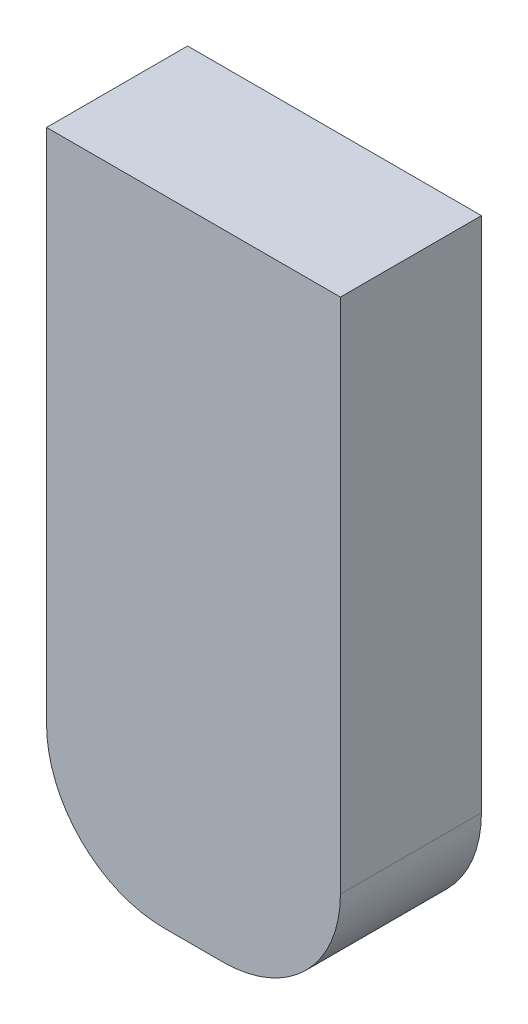
SolidWorks part; units mm, degrees
ref_plane "Front Plane" through (0, 0, 0) normal (0, 0, 1) x (1, 0, 0)
ref_plane "Top Plane" through (0, 0, 0) normal (0, 1, 0) x (1, 0, 0)
ref_plane "Right Plane" through (0, 0, 0) normal (1, 0, 0) x (0, 0, -1)
sketch "Sketch1" plane through (0, 0, 0) normal (0, 0, 1) x (1, 0, 0)
  line L1 (0, 0) -> (31.75, 0)
  line L2 (0, 0) -> (0, 68.58)
  line L3 (0, 68.58) -> (31.75, 68.58)
  line L4 (31.75, 0) -> (31.75, 68.58)
  dimension "D1" = 31.75
  dimension "D2" = 68.58
extrude "Boss-Extrude1" add sketch "Sketch1" along normal blind 15.24
fillet "Fillet1" radius 12.7 2 edges at (0, 0, 7.62) (31.75, 0, 7.62)
equation "\"MDF\"= .3"
equation "\"Foamcore\"= .1"
equation "\"GMaterial\"= .6"
equation "\"CutDistance\" = .1"
equation "\"D1@Boss-Extrude1\"=\"GMaterial\""
